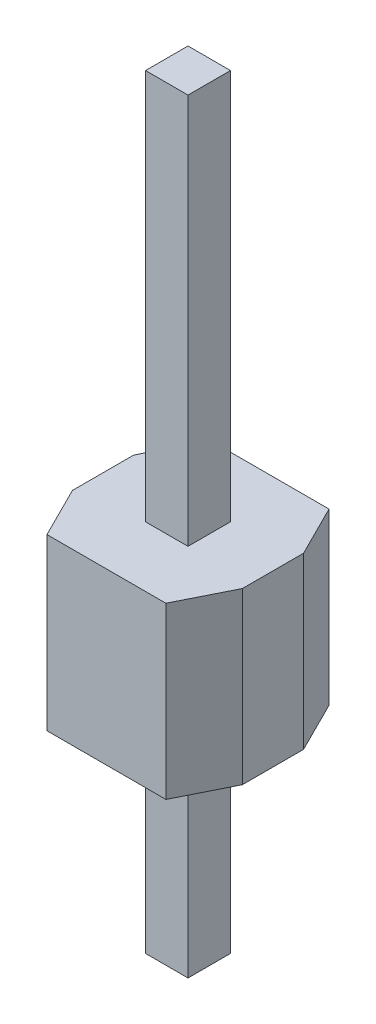
SolidWorks part; units mm, degrees
ref_plane "Front Plane" through (0, 0, 0) normal (0, 0, 1) x (1, 0, 0)
ref_plane "Top Plane" through (0, 0, 0) normal (0, 1, 0) x (1, 0, 0)
ref_plane "Right Plane" through (0, 0, 0) normal (1, 0, 0) x (0, 0, -1)
sketch "Sketch1" plane through (0, 0, 0) normal (0, 1, 0) x (1, 0, 0)
  line L0 (0.381, 0) -> (0, 0.762)
  line L1 (0.381, 0) -> (2.159, 0)
  line L2 (0, 0.762) -> (0, 1.6764)
  line L3 (0.381, 2.4384) -> (2.159, 2.4384)
  line L4 (2.54, 0.762) -> (2.54, 1.6764)
  line L5 (2.159, 0) -> (2.54, 0.762)
  line L6 (0, 1.6764) -> (0.381, 2.4384)
  line L7 (2.54, 1.6764) -> (2.159, 2.4384)
extrude "Boss-Extrude1" add sketch "Sketch1" along normal blind 2.54
sketch "Sketch2" plane through (0, 2.54, 0) normal (0, 1, 0) x (1, 0, 0)
  line L0 (0, 1.6764) -> (0, 0.762) construction
  line L1 (0.9525, 1.5367) -> (1.5875, 1.5367)
  line L2 (0.9525, 1.5367) -> (0.9525, 0.9017)
  line L3 (0.9525, 0.9017) -> (1.5875, 0.9017)
  line L4 (1.5875, 1.5367) -> (1.5875, 0.9017)
  line L6 (2.159, 2.4384) -> (0.381, 2.4384) construction
  dimension "D1" = 0.635
  dimension "D2" = 0.635
  dimension "D3" = 0.9525
  dimension "D4" = 0.9017
extrude "Boss-Extrude2" add sketch "Sketch2" along normal blind 5.842
sketch "Sketch5" plane through (0, 0, 0) normal (0, -1, 0) x (1, 0, 0)
  line L0 (0, -1.6764) -> (0, -0.762) construction
  line L1 (1.5875, -0.9017) -> (0.9525, -0.9017)
  line L2 (1.5875, -0.9017) -> (1.5875, -1.5367)
  line L3 (1.5875, -1.5367) -> (0.9525, -1.5367)
  line L4 (0.9525, -0.9017) -> (0.9525, -1.5367)
  line L5 (0.381, 0) -> (2.159, 0) construction
  dimension "D1" = 0.635
  dimension "D2" = 0.635
  dimension "D3" = 0.9525
  dimension "D4" = 0.9017
extrude "Boss-Extrude3" add sketch "Sketch5" along normal blind 3.048
